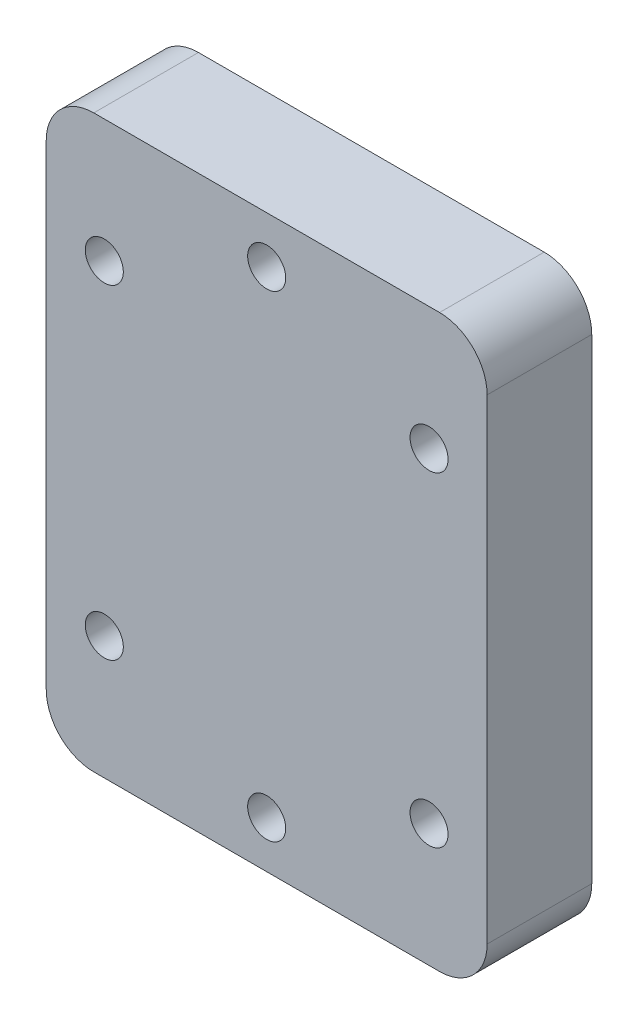
SolidWorks part; units mm, degrees
material "ABS"
ref_plane "X-Y Datum" through (0, 0, 0) normal (0, 0, 1) x (1, 0, 0)
ref_plane "X-Z Datum" through (0, 0, 0) normal (0, 1, 0) x (1, 0, 0)
ref_plane "Y-Z Datum" through (0, 0, 0) normal (1, 0, 0) x (0, 0, -1)
sketch "Sketch1" plane through (0, 0, 0) normal (0, 0, 1) x (1, 0, 0)
  line L0 (0, 30) -> (0, 20.1212) construction
  line L1 (-23.175, 0) -> (23.175, 0) construction
  line L4 (-20, 20) -> (-20, -20) construction
  line L5 (-23.175, -30) -> (23.175, -30)
  line L6 (-23.175, -30) -> (-23.175, 30)
  line L7 (-23.175, 30) -> (23.175, 30)
  line L8 (23.175, -30) -> (23.175, 30)
  line L9 (-23.175, -30) -> (23.175, 30) construction
  line L10 (-23.175, 30) -> (23.175, -30) construction
  line L11 (20, 20) -> (-20, 20) construction
  line L12 (-23.175, 20.1212) -> (23.175, 20.1212) construction
  circle A0 centre (0, 25.0606) radius 2
  circle A1 centre (0, -25.0606) radius 2
  circle A2 centre (17.0711, 17.0711) radius 2 construction
  circle A3 centre (17.0711, -17.0711) radius 2 construction
  circle A4 centre (-17.0711, -17.0711) radius 2 construction
  circle A5 centre (-17.0711, 17.0711) radius 2 construction
  circle A6 centre (17.0711, 17.0711) radius 2
  circle A7 centre (17.0711, -17.0711) radius 2
  circle A8 centre (-17.0711, -17.0711) radius 2
  circle A9 centre (-17.0711, 17.0711) radius 2
  point P2 (0, 0)
  dimension "D3" = 4
  dimension "D1" = 3.175
  dimension "D2" = 10
  dimension "D4" = 4.9394
extrude "Boss-Extrude1" add sketch "Sketch1" against normal blind 9 and the other way blind 2 contours L5 L8 L7 L6 A9 A8 A7 A6 A0 A1
sketch "Sketch2" plane through (0, 0, -9) normal (0, 0, -1) x (-1, 0, 0)
  line L1 (-15, -15) -> (15, -15)
  line L2 (-15, -15) -> (-15, 15)
  line L3 (-15, 15) -> (15, 15)
  line L4 (15, -15) -> (15, 15)
  line L5 (-15, -15) -> (15, 15) construction
  line L6 (-15, 15) -> (15, -15) construction
  point P0 (0, 0)
  dimension "D1" = 30
  dimension "D2" = 30
extrude "Cut-Extrude1" cut sketch "Sketch2" against normal blind 6.35
sketch "Sketch4" plane through (0, 0, -9) normal (0, 0, -1) x (-1, 0, 0)
  circle A0 centre (-17.0711, 17.0711) radius 2
  circle A1 centre (17.0711, 17.0711) radius 2
  circle A2 centre (-17.0711, -17.0711) radius 2
  circle A3 centre (17.0711, -17.0711) radius 2
extrude "Boss-Extrude4" add sketch "Sketch4" against normal blind 0.85
fillet "Fillet1" radius 5 4 edges at (23.175, 30, -3.5) (-23.175, 30, -3.5) (-23.175, -30, -3.5) (23.175, -30, -3.5)
